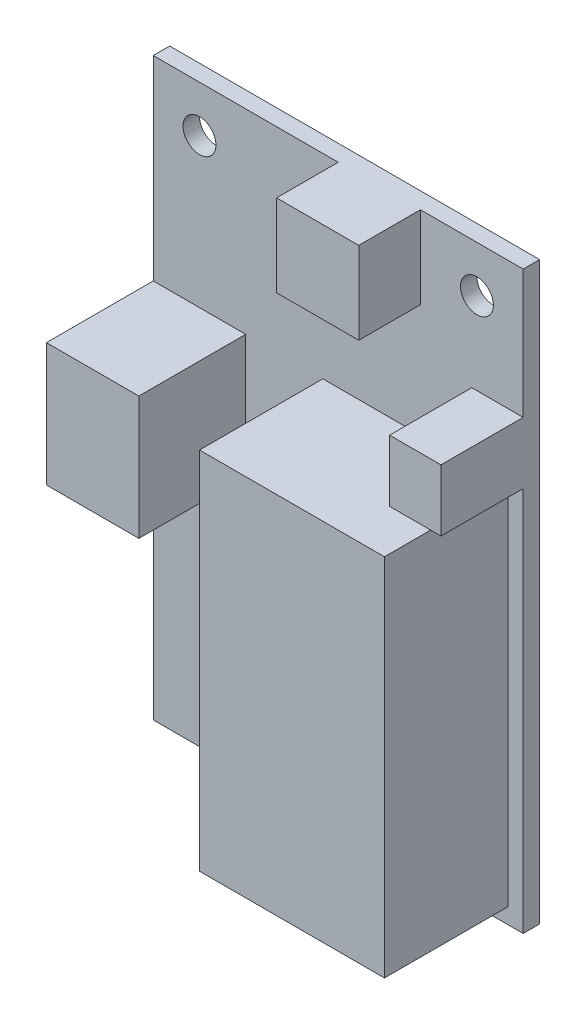
SolidWorks part; units mm, degrees
ref_plane "Plan de face" through (0, 0, 0) normal (0, 0, 1) x (1, 0, 0)
ref_plane "Plan de dessus" through (0, 0, 0) normal (0, 1, 0) x (1, 0, 0)
ref_plane "Plan de droite" through (0, 0, 0) normal (1, 0, 0) x (0, 0, -1)
sketch "Esquisse1" plane through (0, 0, 0) normal (0, 0, 1) x (1, 0, 0)
  line L0 (-31.5, 51.5) -> (-4.5, 51.5) construction
  line L1 (-36, 56) -> (0, 56)
  line L2 (-36, 56) -> (-36, 0)
  line L3 (-36, 0) -> (0, 0)
  line L4 (0, 56) -> (0, 0)
  circle A0 centre (-31.5, 51.5) radius 1.6
  circle A1 centre (-4.5, 51.5) radius 1.6
  point P8 (-18, 51.5)
  point P9 (-18, 56)
  point P10 (0, 0)
  dimension "D3" = 3.2
  dimension "D1" = 36
  dimension "D2" = 56
  dimension "D4" = 27
  dimension "D5" = 4.5
extrude "Board" add sketch "Esquisse1" along normal blind 1.6
sketch "Esquisse2" plane through (0, 0, 1.6) normal (0, 0, 1) x (1, 0, 0)
  line L0 (0, 56) -> (-36, 56) construction
  line L1 (-18, 56) -> (-10, 56)
  line L2 (-18, 56) -> (-18, 48)
  line L3 (-18, 48) -> (-10, 48)
  line L4 (-10, 56) -> (-10, 48)
  line L5 (-36, 56) -> (-36, 0) construction
  dimension "D1" = 18
  dimension "D2" = 8
  dimension "D3" = 8
extrude "RS232" add sketch "Esquisse2" along normal blind 6
sketch "Esquisse3" plane through (0, 0, 1.6) normal (0, 0, 1) x (1, 0, 0)
  line L0 (0, 0) -> (0, 56) construction
  line L1 (0, 43.5) -> (-5, 43.5)
  line L2 (0, 43.5) -> (0, 37.5)
  line L3 (0, 37.5) -> (-5, 37.5)
  line L4 (-5, 43.5) -> (-5, 37.5)
  line L5 (0, 56) -> (-10, 56) construction
  dimension "D1" = 12.5
  dimension "D2" = 6
  dimension "D3" = 5
extrude "Limit switch" add sketch "Esquisse3" along normal blind 8
sketch "Esquisse4" plane through (0, 0, 1.6) normal (0, 0, 1) x (1, 0, 0)
  line L0 (-36, 56) -> (-36, 0) construction
  line L1 (-19.5, 37) -> (-1.5, 37)
  line L2 (-19.5, 37) -> (-19.5, 1.5)
  line L3 (-19.5, 1.5) -> (-1.5, 1.5)
  line L4 (-1.5, 37) -> (-1.5, 1.5)
  line L5 (-18, 56) -> (-36, 56) construction
  dimension "D1" = 16.5
  dimension "D2" = 19
  dimension "D3" = 35.5
  dimension "D4" = 18
extrude "Teensy 4.0" add sketch "Esquisse4" along normal blind 12
sketch "Esquisse5" plane through (0, 0, 1.6) normal (0, 0, 1) x (1, 0, 0)
  line L0 (-18, 56) -> (-36, 56) construction
  line L1 (-36, 37) -> (-27, 37)
  line L2 (-36, 37) -> (-36, 25)
  line L3 (-36, 25) -> (-27, 25)
  line L4 (-27, 37) -> (-27, 25)
  line L5 (-36, 56) -> (-36, 0) construction
  point P6 (-36, 37)
  dimension "D1" = 9
  dimension "D2" = 12
  dimension "D3" = 19
extrude "5v regulator" add sketch "Esquisse5" along normal blind 10.4
